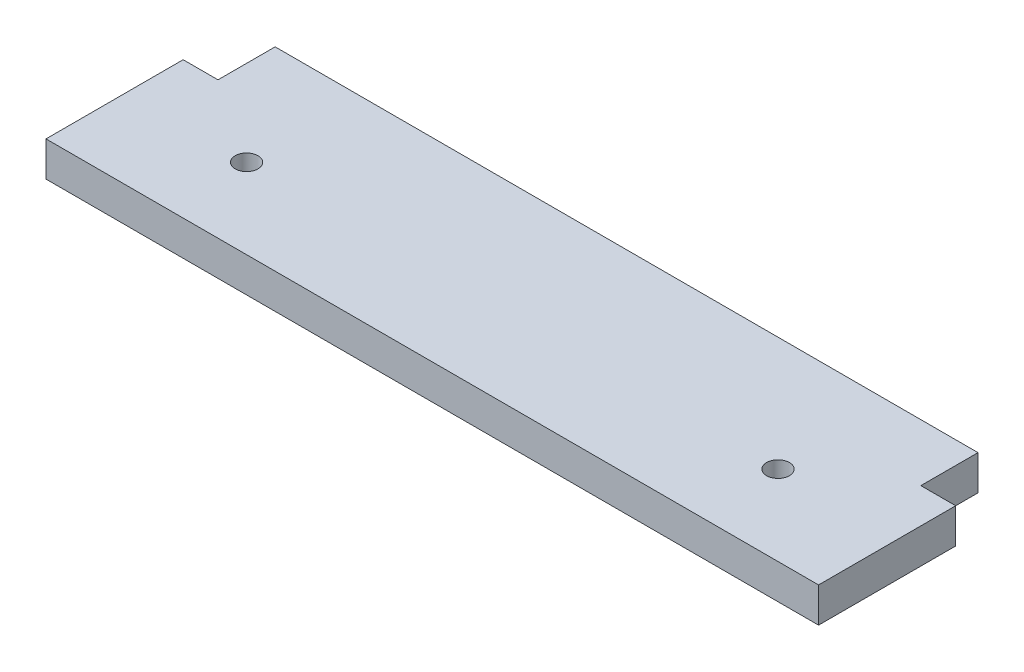
SolidWorks part; units mm, degrees
ref_plane "Front Plane" through (0, 0, 0) normal (0, 0, 1) x (1, 0, 0)
ref_plane "Top Plane" through (0, 0, 0) normal (0, 1, 0) x (1, 0, 0)
ref_plane "Right Plane" through (0, 0, 0) normal (1, 0, 0) x (0, 0, -1)
sketch "Sketch1" plane through (0, 0, 0) normal (0, 1, 0) x (1, 0, 0)
  line L1 (0, 0) -> (67.6, 0)
  line L2 (0, 0) -> (0, 17)
  line L3 (0, 17) -> (67.6, 17)
  line L4 (67.6, 0) -> (67.6, 17)
  line L7 (0, 12) -> (3.05, 12)
  line L8 (3.05, 17) -> (3.05, 12)
  line L11 (67.6, 12) -> (64.55, 12)
  line L12 (64.55, 17) -> (64.55, 12)
  line L13 (0, 0) -> (10.55, 0)
  line L14 (0, 0) -> (0, 7)
  line L15 (0, 7) -> (10.55, 7)
  line L16 (10.55, 0) -> (10.55, 7)
  line L17 (67.6, 0) -> (57.05, 0)
  line L18 (67.6, 0) -> (67.6, 7)
  line L19 (67.6, 7) -> (57.05, 7)
  line L20 (57.05, 0) -> (57.05, 7)
  circle A0 centre (10.55, 7) radius 1
  circle A1 centre (57.05, 7) radius 1
  dimension "D9" = 2
  dimension "D12" = 2
  dimension "D1" = 17
  dimension "D2" = 67.6
  dimension "D3" = 5
  dimension "D4" = 3.05
  dimension "D5" = 5
  dimension "D6" = 3.05
  dimension "D7" = 10.55
  dimension "D8" = 7
  dimension "D10" = 7
  dimension "D11" = 10.55
extrude "Boss-Extrude1" add sketch "Sketch1" along normal blind 3.05 contours L12 L3 L8 L7 L2 L1 L4 L11 | A0 L15 L2 L1 L16 | A1 L20 L1 L4 L19
